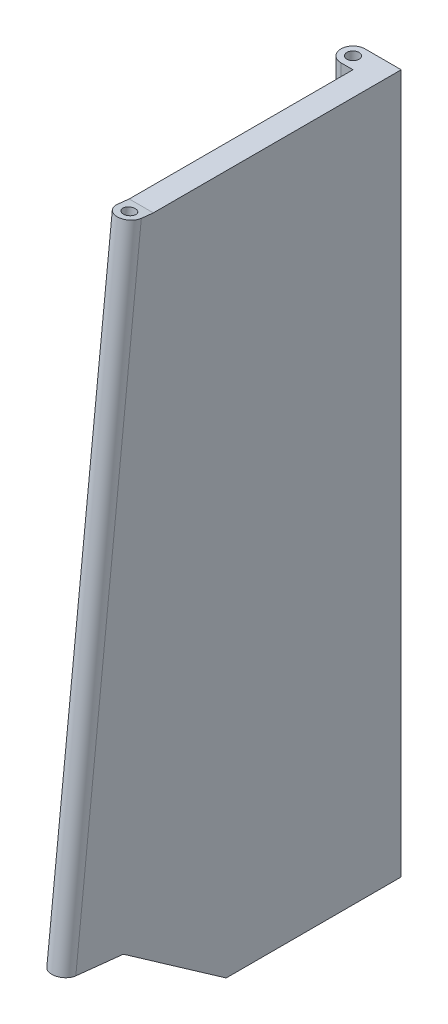
SolidWorks part; units mm, degrees
ref_plane "Спереди" through (0, 0, 0) normal (0, 0, 1) x (1, 0, 0)
ref_plane "Сверху" through (0, 0, 0) normal (0, 1, 0) x (1, 0, 0)
ref_plane "Справа" through (0, 0, 0) normal (1, 0, 0) x (0, 0, -1)
sketch "Эскиз1" plane through (0, 0, 0) normal (1, 0, 0) x (0, 0, -1)
  line L0 (-26, 6.2849) -> (-23.0512, 5.9749)
  line L1 (-14.5181, 0) -> (0, 0)
  line L2 (0, 0) -> (0, 58)
  line L3 (0, 58) -> (-20.5645, 58)
  line L4 (-20.5645, 58) -> (-26, 6.2849)
  line L5 (50, 0) -> (-50, 0) construction
  line L6 (0, 50) -> (0, -50) construction
  line L8 (-14.5181, 0) -> (-23.0512, 5.9749)
  point P5 (-10.2823, 58)
  point P6 (-7.2591, 0)
  dimension "D1" = 52
  dimension "D2" = 84
  dimension "D3" = 26
  dimension "D4" = 58
  dimension "D5" = 90
  dimension "D6" = 145
extrude "Бобышка-Вытянуть1" add sketch "Эскиз1" along normal blind 2
sketch "Эскиз2" plane through (0, 0, 0) normal (0, 1, 0) x (1, 0, 0)
  line L0 (-50, 0) -> (50, 0) construction
  line L1 (0, 1) -> (0, 0)
  line L2 (0, 0) -> (2, 0)
  line L3 (2, 0) -> (2, 1)
  circle A0 centre (1, 1) radius 0.5
  arc A1 (0, 1) -> (2, 1) centre (1, 1) cw
  dimension "D1" = 1
  dimension "D2" = 1
extrude "Бобышка-Вытянуть2" [suppressed] add sketch "Эскиз2" along normal blind 58
sketch "Эскиз3" plane through (0, 3.5133, -0.3693) normal (0, -0.9945, 0.1045) x (1, 0, 0)
  line L0 (2, 26.5145) -> (0, 26.5145) construction
  line L1 (0, 26.5145) -> (0, 27.5145)
  line L2 (0, 26.5145) -> (2, 26.5145)
  line L3 (2, 26.5145) -> (2, 23.5495) construction
  line L4 (2, 26.5145) -> (2, 27.5145)
  circle A0 centre (1, 27.5145) radius 0.5
  arc A1 (0, 27.5145) -> (2, 27.5145) centre (1, 27.5145) cw
  dimension "D1" = 1
  dimension "D2" = 1
extrude "Бобышка-Вытянуть3" add sketch "Эскиз3" against normal blind 52
sketch "Эскиз4" plane through (0, 0, 0) normal (0, 1, 0) x (1, 0, 0)
  line L1 (-1, 0) -> (0, 0)
  line L2 (0, -14.5181) -> (0, 0) construction
  line L3 (0, -2) -> (-1, -2)
  line L4 (0, -2) -> (0, 0)
  circle A0 centre (-1, -1) radius 0.5
  arc A1 (-1, -2) -> (-1, 0) centre (-1, -1) cw
  dimension "D1" = 1
  dimension "D2" = 1
  dimension "D3" = 2
extrude "Бобышка-Вытянуть4" add sketch "Эскиз4" along normal up to surface (58 mm away) up to face at (1, 58, 10.2823)
